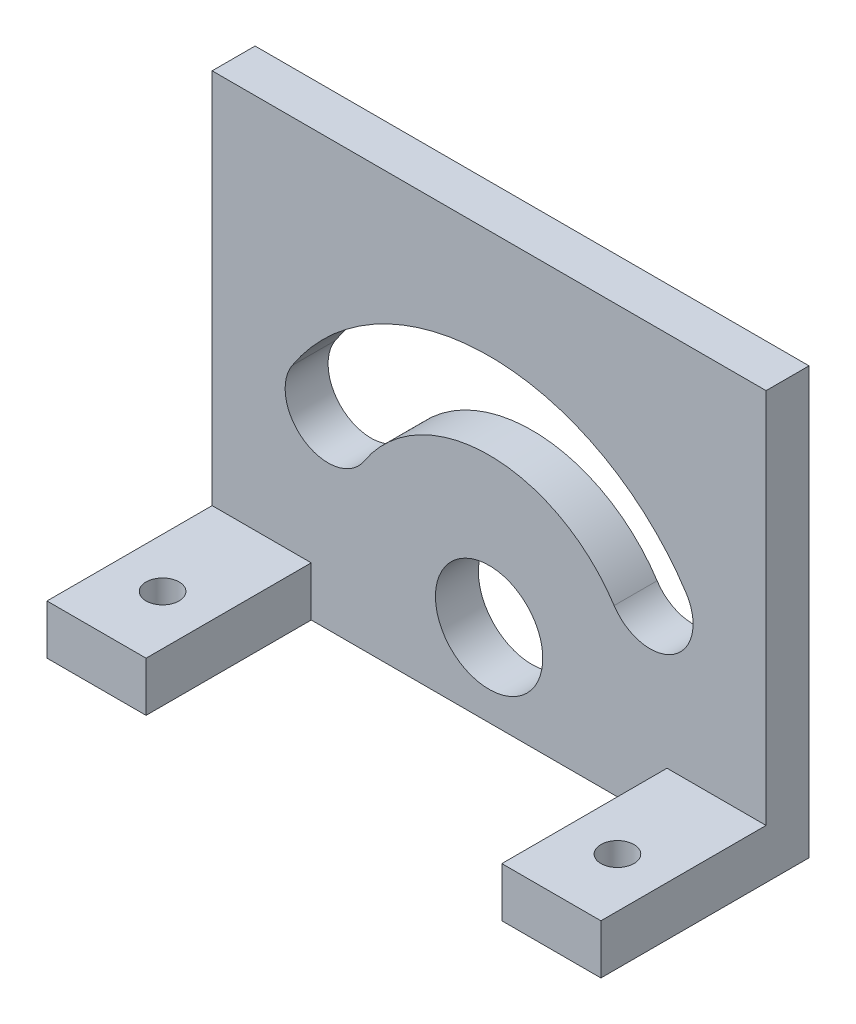
SolidWorks part; units mm, degrees
ref_plane "Plan de face" through (0, 0, 0) normal (0, 0, 1) x (1, 0, 0)
ref_plane "Plan de dessus" through (0, 0, 0) normal (0, 1, 0) x (1, 0, 0)
ref_plane "Plan de droite" through (0, 0, 0) normal (1, 0, 0) x (0, 0, -1)
sketch "Esquisse1" plane through (0, 0, 0) normal (0, 0, 1) x (1, 0, 0)
  line L0 (15.875, -11.8) -> (17.7, -11.8)
  line L1 (0, 0) -> (9.275, 0)
  line L2 (0, 0) -> (0, -11.8)
  line L3 (0, -11.8) -> (6.625, -11.8)
  line L4 (17.7, 0) -> (17.7, -11.8)
  line L5 (9.275, 0) -> (9.275, -1.925) construction
  line L6 (15.875, -11.8) -> (15.875, -13.9)
  line L7 (15.875, -13.9) -> (6.625, -13.9)
  line L8 (6.625, -11.8) -> (6.625, -13.9)
  line L9 (13.225, 0) -> (13.225, -1.925) construction
  line L10 (13.225, 0) -> (17.7, 0)
  line L11 (9.275, 0) -> (13.225, 0)
  arc A0 (9.275, -1.925) -> (13.225, -1.925) centre (11.25, -1.925) ccw construction
  point P10 (11.25, -13.9)
  dimension "D6" = 3.95
  dimension "D1" = 17.7
  dimension "D2" = 11.8
  dimension "D3" = 9.25
  dimension "D4" = 6.45
  dimension "D5" = 2.1
  dimension "D7" = 9.875
extrude "Boss.-Extru.1" add sketch "Esquisse1" along normal blind 1
sketch "Esquisse2" plane through (0, 0, 0) normal (0, 0, -1) x (-1, 0, 0)
  line L0 (-13.225, 0) -> (-17.7, 0) construction
  circle A0 centre (-15.4625, -1.925) radius 1.225
  point P4 (-15.4625, 0)
  dimension "D1" = 2.45
extrude "Boss.-Extru.2" [suppressed] add sketch "Esquisse2" along normal blind 0.1
sketch "Esquisse3" plane through (0, 0, 0) normal (0, 0, -1) x (-1, 0, 0)
  line L0 (-15.875, -13.9) -> (-6.625, -13.9) construction
  circle A0 centre (-11.25, -8) radius 1.25
  dimension "D1" = 5.9
  dimension "D2" = 2.5
extrude "Enlèv. mat.-Extru.1" cut sketch "Esquisse3" against normal blind 3.45
sketch "Esquisse5" plane through (0, 0, 0) normal (0, 0, -1) x (-1, 0, 0)
  line L0 (-15, -5.558) -> (-7.5, -5.558) construction
  circle A0 centre (-11.25, -8) radius 4.475 construction
  arc A1 (-6.662, -5.0124) -> (-15.838, -5.0124) centre (-11.25, -8) ccw
  arc A2 (-8.338, -6.1037) -> (-14.162, -6.1037) centre (-11.25, -8) ccw
  arc A3 (-15.838, -5.0124) -> (-14.162, -6.1037) centre (-15, -5.558) ccw
  arc A4 (-8.338, -6.1037) -> (-6.662, -5.0124) centre (-7.5, -5.558) ccw
  circle A6 centre (-11.25, -8) radius 3.475 construction
  circle A7 centre (-11.25, -8) radius 5.475 construction
  point P6 (-5.775, -8)
  point P11 (-11.25, -5.558)
  point P12 (-7.775, -8)
  dimension "D1" = 8.95
  dimension "D4" = 7.5
  dimension "D2" = 1
  dimension "D3" = 1
extrude "Enlèv. mat.-Extru.2" cut sketch "Esquisse5" against normal blind 3.45
sketch "Esquisse7" [suppressed] plane through (0, 0, -0.1) normal (0, 0, -1) x (-1, 0, 0)
  circle A0 centre (-15.4625, -1.925) radius 0.575
  dimension "D1" = 1.15
extrude "Boss.-Extru.4" [suppressed] add sketch "Esquisse7" along normal blind 1
scale "Scale1" scale about centroid uniform scaling yes scale factor 6.5
sketch "Sketch1" plane through (0, 0, -2.75) normal (0, 0, -1) x (-1, 0, 0)
  line L0 (-66.793, -40.0242) -> (-66.793, 36.6758) construction
  line L1 (-66.793, -27.8242) -> (17.057, -27.8242)
  line L2 (-66.793, -27.8242) -> (-66.793, -58.0986)
  line L3 (-66.793, -58.0986) -> (48.257, -58.0986)
  line L4 (48.257, -27.8242) -> (48.257, -58.0986)
  line L5 (-66.793, 36.6758) -> (48.257, 36.6758) construction
  line L7 (48.257, 36.6758) -> (17.057, 36.6758)
  line L8 (48.257, 36.6758) -> (48.257, -27.8242)
  line L10 (17.057, 36.6758) -> (17.057, -27.8242)
  circle A0 centre (-24.868, -15.3242) radius 8.125 construction
  dimension "D2" = 41.925
  dimension "D1" = 64.5
extrude "Cut-Extrude1" cut sketch "Sketch1" against normal through all both and the other way through all
sketch "Sketch2" plane through (0, -27.8242, 0) normal (0, -1, 0) x (1, 0, 0)
  line L1 (-17.057, 3.75) -> (-2.057, 3.75)
  line L2 (-17.057, 3.75) -> (-17.057, 28.75)
  line L3 (-17.057, 28.75) -> (-2.057, 28.75)
  line L4 (-2.057, 3.75) -> (-2.057, 28.75)
  line L5 (66.793, 3.75) -> (51.793, 3.75)
  line L6 (66.793, 3.75) -> (66.793, 28.75)
  line L7 (66.793, 28.75) -> (51.793, 28.75)
  line L8 (51.793, 3.75) -> (51.793, 28.75)
  dimension "D1" = 15
  dimension "D2" = 25
extrude "Boss-Extrude1" add sketch "Sketch2" against normal blind 7.5
sketch "Sketch3" plane through (0, -20.3242, 0) normal (0, 1, 0) x (1, 0, 0)
  line L0 (-2.057, -28.75) -> (-17.057, -28.75) construction
  line L1 (-17.057, -28.75) -> (-17.057, -3.75) construction
  line L2 (24.868, -3.75) -> (24.868, -29.1418) construction
  line L3 (66.793, -3.75) -> (-17.057, -3.75) construction
  circle A0 centre (-9.557, -18.75) radius 2.5
  circle A1 centre (59.293, -18.75) radius 2.5
  dimension "D1" = 5
  dimension "D2" = 10
  dimension "D3" = 7.5
extrude "Cut-Extrude3" cut sketch "Sketch3" against normal through all
